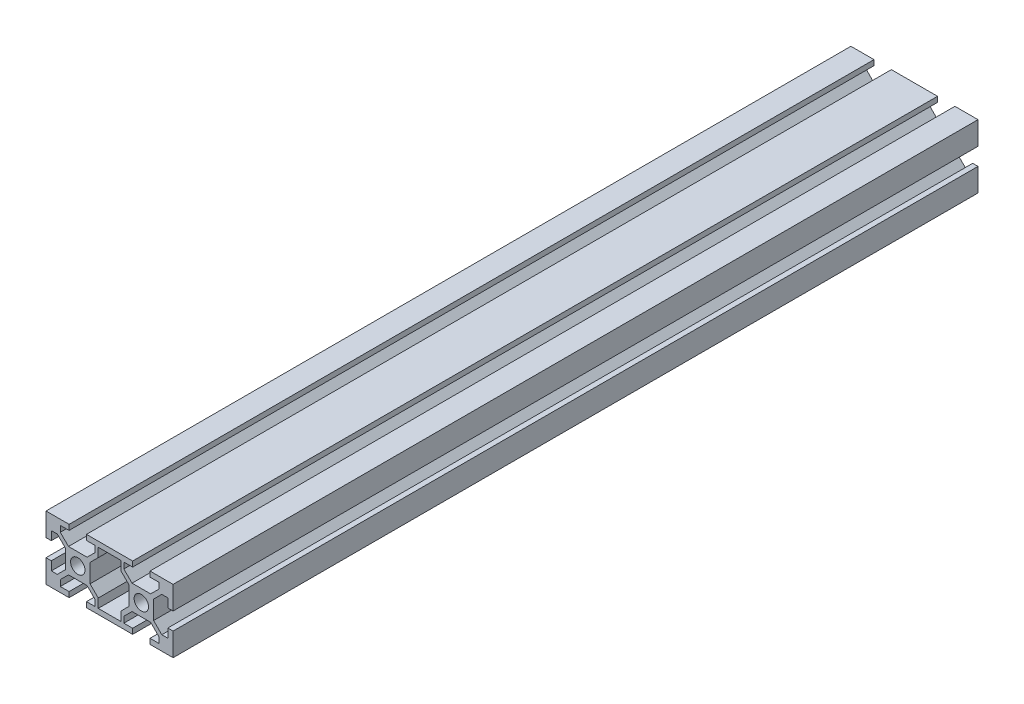
SolidWorks part; units mm, degrees
ref_plane "前视基准面" through (0, 0, 0) normal (0, 0, 1) x (1, 0, 0)
ref_plane "上视基准面" through (0, 0, 0) normal (0, 1, 0) x (1, 0, 0)
ref_plane "右视基准面" through (0, 0, 0) normal (1, 0, 0) x (0, 0, -1)
sketch "草图1" plane through (0, 0, 0) normal (0, 0, 1) x (1, 0, 0)
  line L0 (-4.1, 15) -> (-4.1, 12.5)
  line L1 (-4.3858, -5.8) -> (4.3858, -5.8)
  line L2 (-5.8, -4.3858) -> (-5.8, 4.3858)
  line L3 (-4.3858, 5.8) -> (4.3858, 5.8)
  line L4 (5.8, -4.3858) -> (5.8, 4.3858)
  line L5 (-9.6642, 8.25) -> (-12.5, 8.25)
  line L6 (-8.25, -12.5) -> (-4.1, -12.5)
  line L7 (-15, -15) -> (-4.1, -15)
  line L8 (-15, -15) -> (-15, -4.1)
  line L9 (-8.25, 15) -> (-4.1, 15)
  line L10 (9.6642, -8.25) -> (9.6642, -12.5)
  line L11 (-8.25, 9.6642) -> (-8.25, 12.5)
  line L12 (-8.25, 15) -> (-15, 15)
  line L13 (9.6642, -12.5) -> (20.3358, -12.5)
  line L14 (8.25, 9.6642) -> (8.25, 12.5)
  line L15 (8.25, 15) -> (15, 15)
  line L16 (20.3358, -12.5) -> (20.3358, -8.25)
  line L17 (9.6642, 8.25) -> (9.6642, 12.5)
  line L18 (8.25, -9.6642) -> (8.25, -12.5)
  line L19 (8.25, -15) -> (15, -15)
  line L20 (9.6642, 12.5) -> (20.3358, 12.5)
  line L21 (-15, 8.25) -> (-15, 15)
  line L22 (-9.6642, -8.25) -> (-12.5, -8.25)
  line L23 (-8.25, -9.6642) -> (-8.25, -12.5)
  line L24 (-8.25, -15) -> (-15, -15)
  line L25 (-15, -8.25) -> (-15, -15)
  line L26 (-12.5, -8.25) -> (-12.5, -4.1)
  line L27 (-8.25, 12.5) -> (-4.1, 12.5)
  line L28 (20.3358, 12.5) -> (20.3358, 8.25)
  line L29 (-8.25, 9.6642) -> (-4.3858, 5.8)
  line L30 (-9.6642, 8.25) -> (-5.8, 4.3858)
  line L31 (8.25, 9.6642) -> (4.3858, 5.8)
  line L32 (9.6642, 8.25) -> (5.8, 4.3858)
  line L33 (4.3858, -5.8) -> (8.25, -9.6642)
  line L34 (-5.8, -4.3858) -> (-9.6642, -8.25)
  line L35 (4.1, 15) -> (4.1, 12.5)
  line L36 (5.8, -4.3858) -> (9.6642, -8.25)
  line L37 (-4.3858, -5.8) -> (-8.25, -9.6642)
  line L38 (4.1, 15) -> (15, 15)
  line L39 (4.1, 12.5) -> (8.25, 12.5)
  line L40 (-4.1, -12.5) -> (-4.1, -15)
  line L41 (4.1, -15) -> (15, -15)
  line L42 (4.1, -12.5) -> (8.25, -12.5)
  line L43 (4.1, -12.5) -> (4.1, -15)
  line L44 (-15, 4.1) -> (-12.5, 4.1)
  line L45 (-15, -4.1) -> (-12.5, -4.1)
  line L46 (-15, 4.1) -> (-15, 15)
  line L47 (-12.5, 4.1) -> (-12.5, 8.25)
  line L48 (-15, -15) -> (0, 0) construction
  line L52 (-15, 8.25) -> (-15, 4.1)
  line L54 (8.25, -15) -> (4.1, -15)
  line L55 (8.25, 15) -> (4.1, 15)
  line L56 (38.25, 9.6642) -> (38.25, 12.5)
  line L57 (21.75, 9.6642) -> (25.6142, 5.8)
  line L58 (38.25, -15) -> (34.1, -15)
  line L59 (25.6142, 5.8) -> (34.3858, 5.8)
  line L61 (34.1, 15) -> (34.1, 12.5)
  line L62 (21.75, 15) -> (15, 15)
  line L63 (39.6642, 8.25) -> (35.8, 4.3858)
  line L64 (45, 4.1) -> (45, 15)
  line L65 (38.25, 15) -> (45, 15)
  line L66 (39.6642, -8.25) -> (42.5, -8.25)
  line L68 (45, -15) -> (45, -4.1)
  line L69 (38.25, -9.6642) -> (38.25, -12.5)
  line L70 (35.8, -4.3858) -> (39.6642, -8.25)
  line L71 (42.5, -4.1) -> (45, -4.1)
  line L72 (45, 8.25) -> (45, 15)
  line L73 (42.5, -8.25) -> (42.5, -4.1)
  line L74 (38.25, 15) -> (34.1, 15)
  line L77 (34.1, 12.5) -> (38.25, 12.5)
  line L79 (38.25, 9.6642) -> (34.3858, 5.8)
  line L80 (34.1, -12.5) -> (38.25, -12.5)
  line L82 (35.8, -4.3858) -> (35.8, 4.3858)
  line L83 (21.75, -15) -> (15, -15)
  line L84 (34.1, -15) -> (45, -15)
  line L85 (21.75, -12.5) -> (25.9, -12.5)
  line L86 (39.6642, 8.25) -> (42.5, 8.25)
  line L87 (24.2, -4.3858) -> (20.3358, -8.25)
  line L88 (42.5, 4.1) -> (45, 4.1)
  line L89 (21.75, 12.5) -> (25.9, 12.5)
  line L90 (15, 4.1) -> (17.5, 4.1)
  line L91 (25.9, 15) -> (25.9, 12.5)
  line L92 (21.75, 9.6642) -> (21.75, 12.5)
  line L93 (45, -8.25) -> (45, -15)
  line L94 (34.1, 15) -> (45, 15)
  line L96 (20.3358, 8.25) -> (24.2, 4.3858)
  line L97 (34.1, -12.5) -> (34.1, -15)
  line L98 (45, 8.25) -> (45, 4.1)
  line L99 (24.2, -4.3858) -> (24.2, 4.3858)
  line L100 (21.75, -9.6642) -> (21.75, -12.5)
  line L101 (25.9, -12.5) -> (25.9, -15)
  line L102 (15, -15) -> (25.9, -15)
  line L103 (34.3858, -5.8) -> (38.25, -9.6642)
  line L104 (42.5, 4.1) -> (42.5, 8.25)
  line L105 (25.6142, -5.8) -> (34.3858, -5.8)
  line L108 (21.75, 15) -> (25.9, 15)
  line L109 (38.25, -15) -> (45, -15)
  line L110 (25.6142, -5.8) -> (21.75, -9.6642)
  circle A0 centre (0, 0) radius 3.4
  circle A1 centre (30, 0) radius 3.4
extrude "凸台-拉伸1" add sketch "草图1" along normal blind 380
